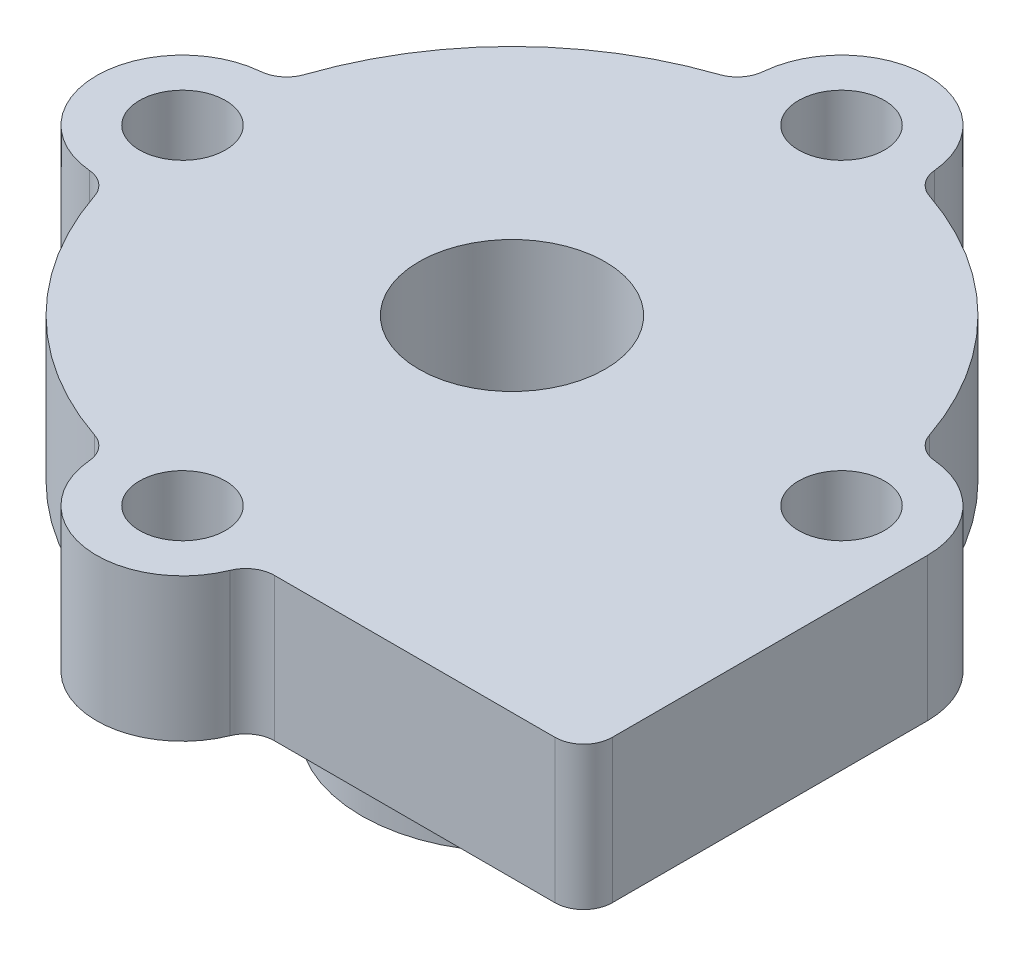
SolidWorks part; units mm, degrees
ref_plane "Front Plane" through (0, 0, 0) normal (0, 0, 1) x (1, 0, 0)
ref_plane "Top Plane" through (0, 0, 0) normal (0, 1, 0) x (1, 0, 0)
ref_plane "Right Plane" through (0, 0, 0) normal (1, 0, 0) x (0, 0, -1)
sketch "Sketch1" plane through (0, 0, 0) normal (0, 1, 0) x (1, 0, 0)
  circle A0 centre (0, 0) radius 11.5
  circle A1 centre (0, 0) radius 3.25
  dimension "D1" = 23
  dimension "D2" = 6.5
extrude "Boss-Extrude1" add sketch "Sketch1" along normal blind 5
sketch "Sketch3" plane through (0, 0, 0) normal (0, 1, 0) x (1, 0, 0)
  line L0 (0, -6.875) -> (0, 6.875) construction
  circle A0 centre (0, 11.5) radius 3
  circle A1 centre (0, 0) radius 11.5 construction
  dimension "D1" = 6
extrude "Boss-Extrude2" add sketch "Sketch3" along normal blind 5
sketch "Sketch4" plane through (0, 5, 0) normal (0, 1, 0) x (1, 0, 0)
  circle A0 centre (0, 11.5) radius 1.5
  dimension "D1" = 3
extrude "Cut-Extrude1" cut sketch "Sketch4" against normal blind 5
pattern_circular "CirPattern1" count 4 over 360 about axis through (0, 0, 0) along (0, 1, 0) of "Boss-Extrude2"
sketch "Sketch5" plane through (0, 5, 0) normal (0, 1, 0) x (1, 0, 0)
  line L0 (0, -12) -> (14.5, -12)
  line L1 (14.5, -12) -> (14.5, 0)
  line L2 (14.5, 0) -> (10.2718, 0)
  line L3 (10.2718, 0) -> (0, -12)
  line L4 (7.4833, -12) -> (16, -12) construction
  arc A0 (11.1087, -2.9744) -> (11.1087, 2.9744) centre (11.5, 0) ccw construction
extrude "Boss-Extrude3" add sketch "Sketch5" against normal blind 5
pattern_circular "CirPattern2" count 4 over 360 about axis through (0, 0, 0) along (0, 1, 0) of "Cut-Extrude1"
fillet "Fillet1" [suppressed] radius 1
sketch "Sketch6" plane through (0, 0, 0) normal (0, -1, 0) x (1, 0, 0)
  circle A0 centre (0, 0) radius 3.25
  circle A1 centre (0, 0) radius 5.25
  circle A2 centre (0, 0) radius 3.25 construction
  dimension "D1" = 2
extrude "Boss-Extrude4" add sketch "Sketch6" along normal blind 7.5
fillet "Fillet2" radius 1 9 edges at (11.1087, 2.5, -2.9744) (2.9744, 2.5, -11.1087) (-2.9744, 2.5, -11.1087) (-11.1087, 2.5, -2.9744) (-11.1087, 2.5, 2.9744) (-2.9744, 2.5, 11.1087) (14.5, 2.5, 12) (0, 0, 5.25) (2.958, 2.5, 12)
